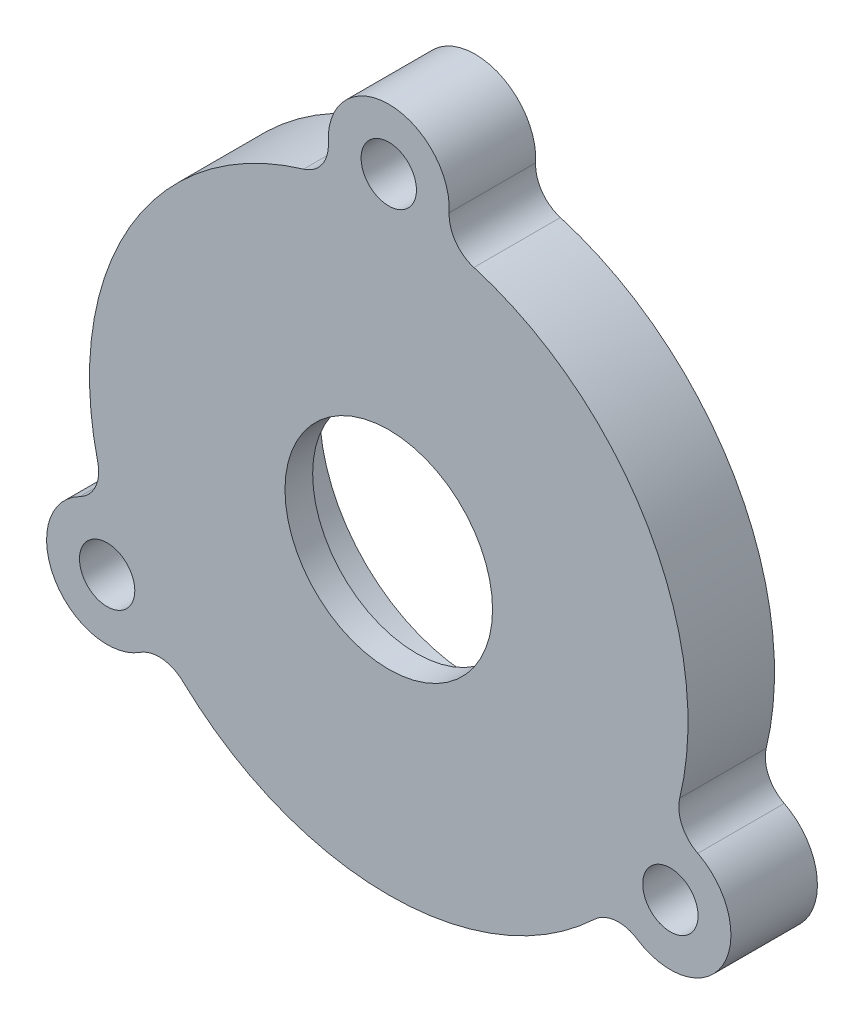
SolidWorks part; units mm, degrees
material "3.1325 (EN-AW 2017A)"
ref_plane "Front Plane" through (0, 0, 0) normal (0, 0, 1) x (1, 0, 0)
ref_plane "Top Plane" through (0, 0, 0) normal (0, 1, 0) x (1, 0, 0)
ref_plane "Right Plane" through (0, 0, 0) normal (1, 0, 0) x (0, 0, -1)
sketch "ｽｹｯﾁ1" plane through (0, 0, 0) normal (0, 0, 1) x (1, 0, 0)
  line L0 (0, 0) -> (0, 22.3977) construction
  circle A0 centre (0, 0) radius 4 construction
  circle A1 centre (0, 0) radius 6
  circle A2 centre (0, 0) radius 12.2 construction
  circle A3 centre (0, 0) radius 15.3 construction
  arc A4 (-3.0218, 17.034) -> (-16.2628, -5.9) centre (0, 0) ccw
  circle A5 centre (0, 18.8) radius 1.6
  arc A6 (3.0218, 17.034) -> (-3.0218, 17.034) centre (0, 18.8) ccw
  arc A7 (13.241, -11.134) -> (16.2628, -5.9) centre (16.2813, -9.4) ccw
  circle A8 centre (16.2813, -9.4) radius 1.6
  arc A9 (-16.2628, -5.9) -> (-13.241, -11.134) centre (-16.2813, -9.4) ccw
  circle A10 centre (-16.2813, -9.4) radius 1.6
  arc A11 (-13.241, -11.134) -> (13.241, -11.134) centre (0, 0) ccw
  arc A12 (16.2628, -5.9) -> (3.0218, 17.034) centre (0, 0) ccw
  point P21 (0, 0)
  dimension "D1" = 8
  dimension "D2" = 12
  dimension "D3" = 24.4
  dimension "D4" = 3.1
  dimension "D5" = 2
  dimension "D6" = 3.2
  dimension "D7" = 7
  dimension "D8" = 3
extrude "ﾎﾞｽ - 押し出し1" add sketch "ｽｹｯﾁ1" along normal blind 5
fillet "ﾌｨﾚｯﾄ1" radius 2 6 edges at (16.2628, -5.9, 2.5) (13.241, -11.134, 2.5) (-13.241, -11.134, 2.5) (-16.2628, -5.9, 2.5) (-3.0218, 17.034, 2.5) (3.0218, 17.034, 2.5)
sketch "ｽｹｯﾁ3" plane through (0, 0, 0) normal (0, 0, -1) x (-1, 0, 0)
  circle A0 centre (0, 0) radius 11.7
  circle A1 centre (0, 0) radius 15.8
  circle A2 centre (0, 0) radius 15.3 construction
  circle A3 centre (0, 0) radius 12.2 construction
  dimension "D1" = 0.5
  dimension "D2" = 0.5
extrude "ｶｯﾄ - 押し出し1" cut sketch "ｽｹｯﾁ3" against normal blind 2.5
sketch "ｽｹｯﾁ4" plane through (0, 0, 0) normal (0, 0, -1) x (-1, 0, 0)
  circle A0 centre (0, 0) radius 9
  dimension "D1" = 18
extrude "ｶｯﾄ - 押し出し2" cut sketch "ｽｹｯﾁ4" against normal offset from surface (3.4 mm away) 1.6 up to face at (17.8813, -9.4, 5)
sketch "ｽｹｯﾁ5" plane through (0, 0, 0) normal (0, 0, -1) x (-1, 0, 0)
  circle A0 centre (0, 18.8) radius 1.6 construction
  circle A1 centre (0, 18.8) radius 1.6
  circle A2 centre (0, 0) radius 18.8
  dimension "D1" = 37.6
